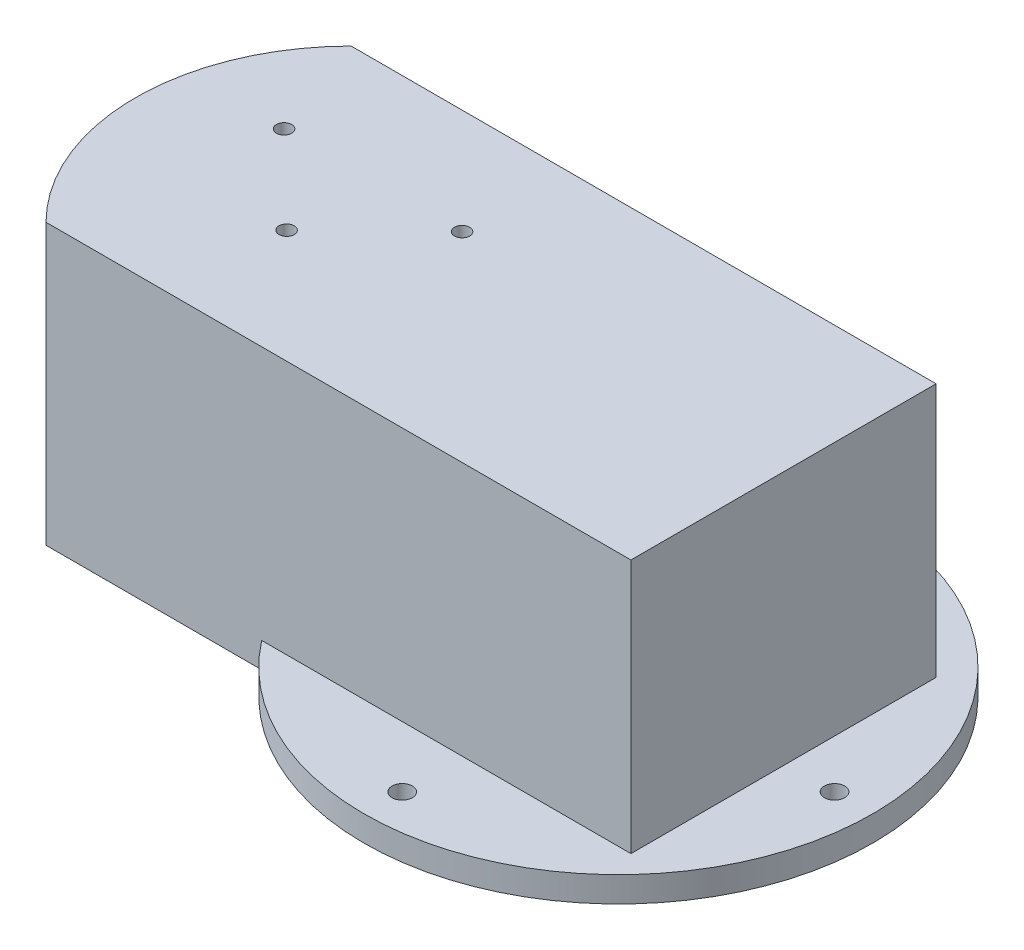
SolidWorks part; units mm, degrees
ref_plane "Front Plane" through (0, 0, 0) normal (0, 0, 1) x (1, 0, 0)
ref_plane "Top Plane" through (0, 0, 0) normal (0, 1, 0) x (1, 0, 0)
ref_plane "Right Plane" through (0, 0, 0) normal (1, 0, 0) x (0, 0, -1)
sketch "Sketch1" plane through (0, 0, 0) normal (0, 1, 0) x (1, 0, 0)
  circle A0 centre (0, 0) radius 50
  dimension "D1" = 100
extrude "Boss-Extrude1" add sketch "Sketch1" along normal blind 5
sketch "Sketch2" plane through (0, 5, 0) normal (0, 1, 0) x (1, 0, 0)
  line L1 (-82, -30.5339) -> (33, -30.5339)
  line L2 (-82, -30.5339) -> (-82, 29.4661)
  line L3 (-82, 29.4661) -> (33, 29.4661)
  line L4 (33, -30.5339) -> (33, 29.4661)
  line L5 (-82, -30.5339) -> (33, 29.4661) construction
  line L6 (-82, 29.4661) -> (33, -30.5339) construction
  circle A1 centre (43, 0) radius 2
  circle A3 centre (0, 0) radius 50 construction
  point P0 (-55, 0)
  circle M3 centre (0, 0) radius 50
  dimension "D3" = 43
  dimension "D4" = 4
  dimension "D1" = 115
  dimension "D2" = 60
  dimension "D5" = 10
extrude "Boss-Extrude2" add sketch "Sketch2" along normal blind 50 and the other way blind 5 contours L1 L4 L3 M3 | L3 L2 L1 M3
sketch "Sketch3" plane through (0, 5, 0) normal (0, 1, 0) x (1, 0, 0)
  circle A0 centre (0, -42.5) radius 2
  arc A1 (-39.594, -30.5339) -> (-40.3949, 29.4661) centre (0, 0) ccw construction
  circle A2 centre (-42.5, 0) radius 2
  circle A3 centre (0, 42.5) radius 2
  circle A4 centre (42.5, 0) radius 2
  point P14 (0, 0)
  dimension "D3" = 4
  dimension "D1" = 42.5
  dimension "D2" = 4
extrude "Cut-Extrude1" cut sketch "Sketch3" against normal blind 50
sketch "Sketch4" plane through (0, 55, 0) normal (0, 1, 0) x (1, 0, 0)
  line L0 (-82, 29.4661) -> (-82, -30.5339)
  arc A0 (-82, -30.5339) -> (-82, 29.4661) centre (-52, -0.5339) cw
extrude "Boss-Extrude3" add sketch "Sketch4" against normal blind 55
sketch "Sketch5" plane through (0, 55, 0) normal (0, 1, 0) x (1, 0, 0)
  line L0 (33, -30.5339) -> (33, 29.4661) construction
  circle A0 centre (-74.5, 8.769) radius 1.5
  circle A1 centre (-39.5, 8.769) radius 1.5
  circle A2 centre (-57, -8.231) radius 1.5
  dimension "D1" = 3
  dimension "D2" = 3
  dimension "D3" = 35
  dimension "8" = 3
  dimension "D4" = 17
  dimension "D5" = 17.5
  dimension "D6" = 90
extrude "Cut-Extrude2" cut sketch "Sketch5" against normal blind 55
